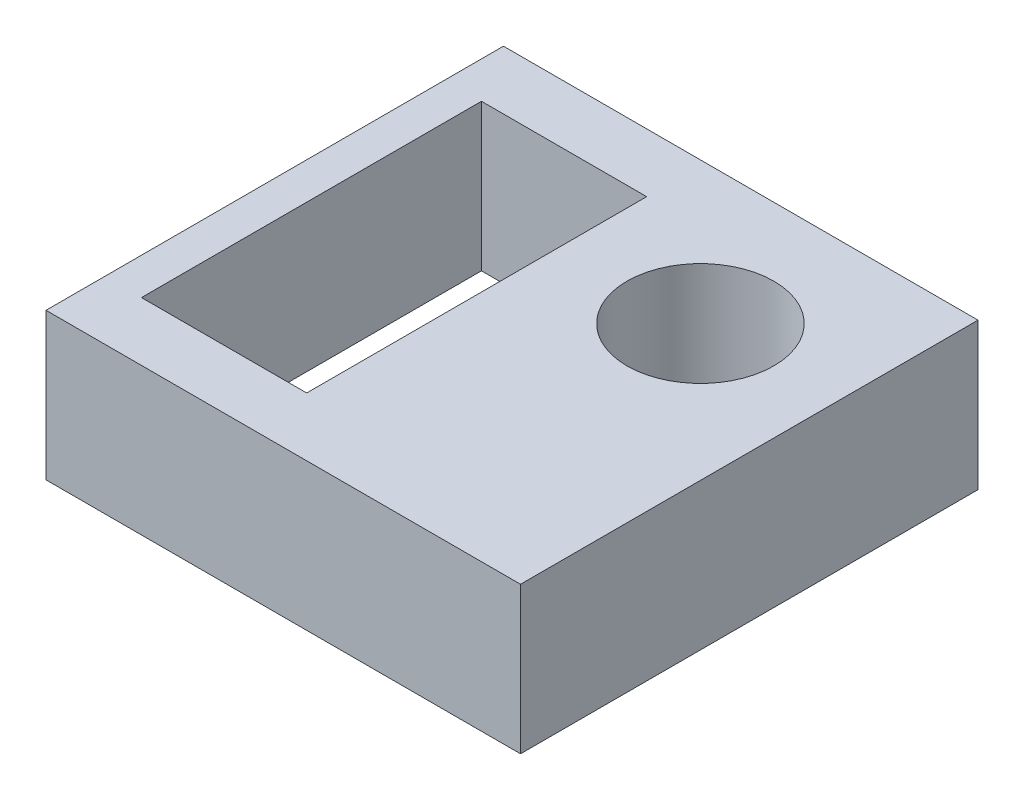
SolidWorks part; units mm, degrees
ref_plane "Front Plane" through (0, 0, 0) normal (0, 0, 1) x (1, 0, 0)
ref_plane "Top Plane" through (0, 0, 0) normal (0, 1, 0) x (1, 0, 0)
ref_plane "Right Plane" through (0, 0, 0) normal (1, 0, 0) x (0, 0, -1)
sketch "Sketch1" plane through (0, 0, 0) normal (0, 1, 0) x (1, 0, 0)
  line L0 (-61.4299, 68.961) -> (-61.4299, 54.61) construction
  line L1 (0, 0) -> (-82.0674, 0)
  line L2 (0, 0) -> (0, 79.121)
  line L3 (0, 79.121) -> (-82.0674, 79.121)
  line L4 (-82.0674, 0) -> (-82.0674, 79.121)
  line L5 (-75.7174, 68.961) -> (-47.1424, 68.961)
  line L6 (-75.7174, 68.961) -> (-75.7174, 10.16)
  line L7 (-75.7174, 10.16) -> (-47.1424, 10.16)
  line L8 (-47.1424, 68.961) -> (-47.1424, 10.16)
  circle A0 centre (-61.4299, 54.61) radius 5.5245 construction
  circle A1 centre (-23.495, 54.61) radius 12.7
  circle A2 centre (-23.495, 54.61) radius 34.0614 construction
  circle A3 centre (-23.495, 54.61) radius 33.2359 construction
  circle A4 centre (-61.4299, 54.61) radius 4.699 construction
  dimension "D6" = 11.049
  dimension "D7" = 25.4
  dimension "D10" = 68.1228
  dimension "D9" = 0.8255
  dimension "D11" = 0.8255
  dimension "D1" = 58.801
  dimension "D2" = 28.575
  dimension "D3" = 10.16
  dimension "D4" = 14.351
  dimension "D5" = 6.35
  dimension "D8" = 23.495
  dimension "D12" = 10.16
extrude "Boss-Extrude1" add sketch "Sketch1" along normal blind 25.4
